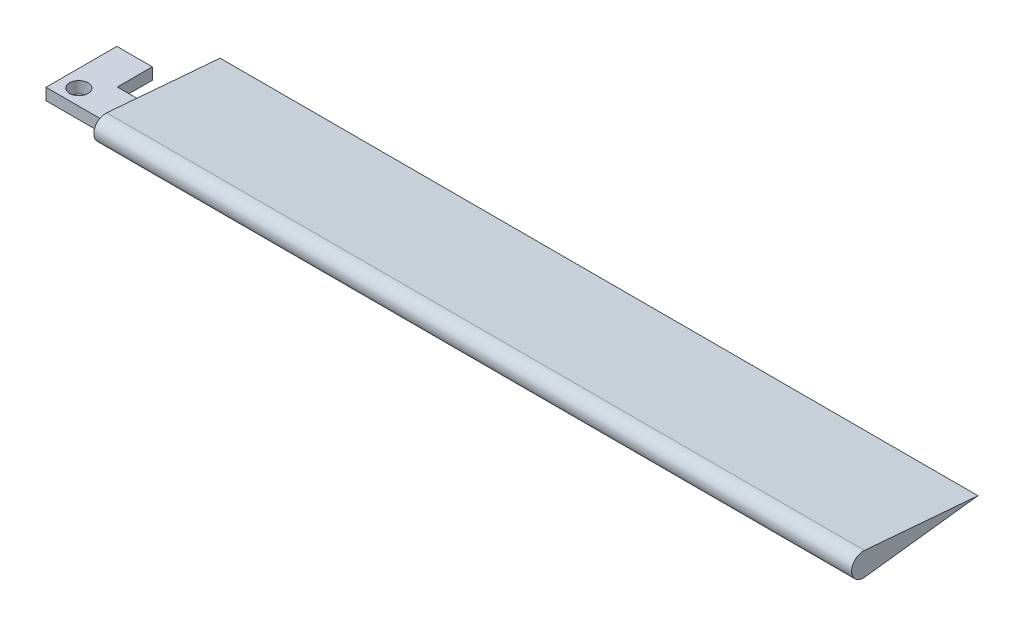
SolidWorks part; units mm, degrees
ref_plane "Front Plane" through (0, 0, 0) normal (0, 0, 1) x (1, 0, 0)
ref_plane "Top Plane" through (0, 0, 0) normal (0, 1, 0) x (1, 0, 0)
ref_plane "Right Plane" through (0, 0, 0) normal (1, 0, 0) x (0, 0, -1)
sketch "Sketch2" plane through (0, 0, 0) normal (1, 0, 0) x (0, 0, -1)
  line L3 (-0.836, 1.6032) -> (-20.2942, 3.2107)
  line L5 (-20.2942, -0.7893) -> (-0.836, 1.6032)
  arc A3 (-20.2942, 3.2107) -> (-20.2942, -0.7893) centre (-20.4987, 1.2107) ccw
  dimension "D2" = 4
extrude "Boss-Extrude2" add sketch "Sketch2" along normal blind 130
sketch "Sketch3" plane through (0, 0, 0) normal (-1, 0, 0) x (0, 0, 1)
  line L1 (14.5472, 2.2107) -> (20.7033, 2.2107)
  line L2 (14.5472, 2.2107) -> (14.5472, 0.2107)
  line L3 (14.5472, 0.2107) -> (20.7033, 0.2107)
  line L4 (20.7033, 2.2107) -> (20.7033, 0.2107)
  dimension "D1" = 1
  dimension "D2" = 1
extrude "Boss-Extrude3" add sketch "Sketch3" along normal blind 10
sketch "Sketch4" plane through (0, 0, 14.5472) normal (0, 0, -1) x (-1, 0, 0)
  line L0 (10, 2.2107) -> (0, 2.2107) construction
  line L1 (3.9223, 2.2107) -> (10, 2.2107)
  line L2 (3.9223, 2.2107) -> (3.9223, 0.2107)
  line L3 (3.9223, 0.2107) -> (10, 0.2107)
  line L4 (10, 2.2107) -> (10, 0.2107)
extrude "Boss-Extrude4" add sketch "Sketch4" along normal blind 6
sketch "Sketch5" plane through (0, 2.2107, 0) normal (0, 1, 0) x (1, 0, 0)
  circle A0 centre (-7.0574, -18.0171) radius 1.5875
  dimension "D1" = 3.175
extrude "Cut-Extrude1" cut sketch "Sketch5" against normal through all
